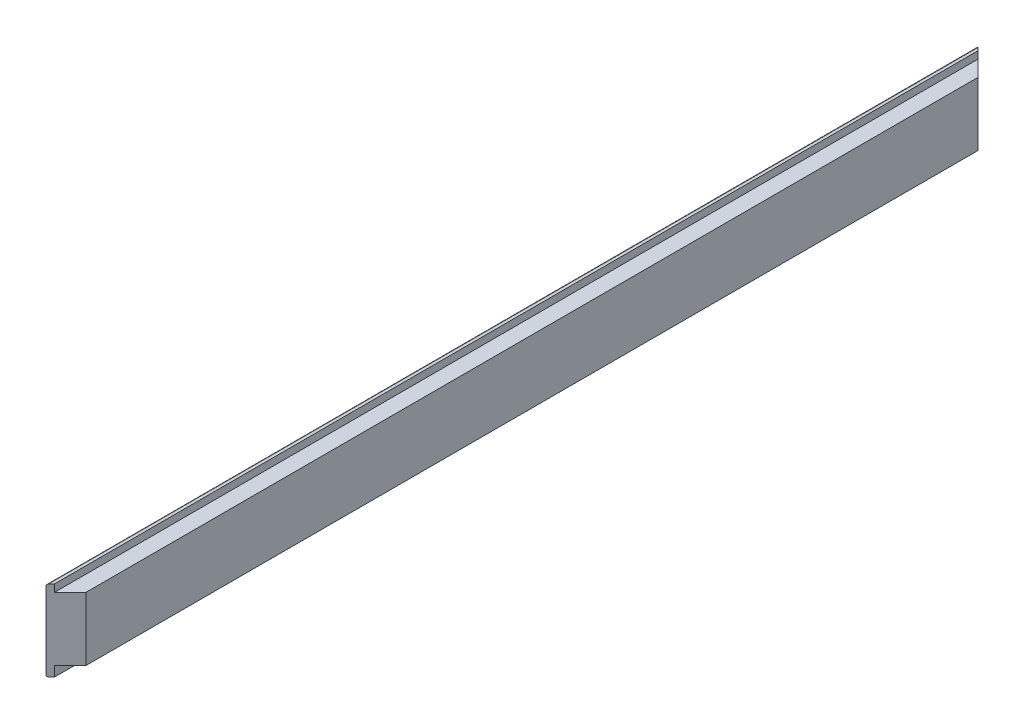
SolidWorks part; units mm, degrees
ref_plane "Front Plane" through (0, 0, 0) normal (0, 0, 1) x (1, 0, 0)
ref_plane "Top Plane" through (0, 0, 0) normal (0, 1, 0) x (1, 0, 0)
ref_plane "Right Plane" through (0, 0, 0) normal (1, 0, 0) x (0, 0, -1)
sketch "Sketch1" plane through (0, 0, 0) normal (0, 0, 1) x (1, 0, 0)
  line L1 (0, 0) -> (19.05, 0)
  line L2 (0, 0) -> (0, 77)
  line L3 (0, 77) -> (19.05, 77)
  line L4 (19.05, 0) -> (19.05, 77)
  line L5 (19.05, 77) -> (4.05, 77)
  line L6 (19.05, 77) -> (19.05, 70)
  line L7 (19.05, 70) -> (4.05, 70)
  line L8 (4.05, 77) -> (4.05, 70)
  line L9 (19.05, 0) -> (4.05, 0)
  line L10 (19.05, 0) -> (19.05, 9.525)
  line L11 (19.05, 9.525) -> (4.05, 9.525)
  line L12 (4.05, 0) -> (4.05, 9.525)
  dimension "D3" = 15
  dimension "D4" = 9.525
  dimension "D5" = 7
  dimension "D1" = 77
  dimension "D2" = 19.05
extrude "Boss-Extrude1" add sketch "Sketch1" along normal mid plane 889.1 contours L1 L12 L11 L4 L7 L8 L3 L2
fillet "Fillet1" radius 1.5875 2 edges at (0, 0, 0) (0, 77, 0)
sketch "Sketch2" plane through (0, 77, 0) normal (0, 1, 0) x (1, 0, 0)
  line L0 (0, -444.55) -> (19.05, -425.5)
  line L1 (19.05, -444.55) -> (19.05, 444.55) construction
  line L2 (19.05, -425.5) -> (19.05, -444.55)
  line L3 (19.05, -444.55) -> (0, -444.55)
  line L4 (0, 444.55) -> (19.05, 425.5)
  line L5 (19.05, 425.5) -> (19.05, 444.55)
  line L6 (19.05, 444.55) -> (0, 444.55)
extrude "Cut-Extrude1" cut sketch "Sketch2" against normal through all both and the other way through all
sketch "Sketch3" plane through (0, 9.525, 0) normal (0, -1, 0) x (1, 0, 0)
  line L0 (11.55, -425.5) -> (11.55, -410.5) construction
  line L1 (19.05, -425.5) -> (4.05, -425.5) construction
  line L3 (10.4775, 0) -> (-10.4775, 0) construction
  line L4 (4.05, 440.5) -> (4.05, -440.5) construction
  point P0 (11.55, -410.5)
  point P13 (11.55, 410.5)
  point P16 (11.55, 0)
  dimension "D1" = 15
hole_wizard "Ø7.9 (7.9) Diameter Hole1" positions "Sketch4" profile "Sketch5" hole size "Ø7.9" standard "ISO"
sketch "Sketch4" plane through (0, 9.525, 0) normal (0, -1, 0) x (-1, 0, 0)
  point P0 (-11.55, -410.5)
  point P3 (-11.55, 410.5)
  point P7 (-11.55, 0)
sketch "Sketch5" plane through (11.55, 9.525, 410.5) normal (1, 0, 0) x (0, 0, -1)
  line L0 (0, 0) -> (0, 17.3734)
  line L1 (0, 17.3734) -> (3.95, 15)
  line L2 (3.95, 15) -> (3.95, 0)
  line L5 (3.95, 0) -> (0, 0)
  line L10 (0, 17.3734) -> (-3.95, 15) construction
  line L11 (0, -6.35) -> (0, 107.95) construction
  dimension "Hole Dia." = 7.9
  dimension "Hole Depth" = 15
  dimension "Drill Angle" = 118
sketch "Sketch6" plane through (0, 0, 0) normal (-1, 0, 0) x (0, 0, 1)
  line L0 (378.1123, 33.9817) -> (356.26, 33.9817) construction
  line L1 (334.55, 50) -> (394.55, 50)
  line L2 (334.55, 50) -> (334.55, 20)
  line L3 (334.55, 20) -> (394.55, 20)
  line L4 (394.55, 50) -> (394.55, 20)
  line L5 (338.2336, 41.8089) -> (346.0737, 41.8089) construction
  line L6 (338.2336, 41.8089) -> (338.2336, 26.1544) construction
  line L7 (338.2336, 26.1544) -> (346.0737, 26.1544) construction
  line L8 (346.0737, 41.8089) -> (346.0737, 26.1544) construction
  line L9 (348.4199, 41.8089) -> (356.26, 41.8089) construction
  line L10 (348.4199, 41.8089) -> (348.4199, 26.1544) construction
  line L11 (348.4199, 26.1544) -> (356.26, 26.1544) construction
  line L12 (356.26, 41.8089) -> (356.26, 26.1544) construction
  line L13 (444.55, 1.5875) -> (444.55, 75.4125) construction
  line L15 (10.4775, 0) -> (-10.4775, 0) construction
  circle A6 centre (378.1123, 33.9817) radius 8.6938 construction
  dimension "D1" = 50
  dimension "D2" = 20
  dimension "D3" = 30
  dimension "D4" = 60
extrude "Cut-Extrude2" [suppressed] cut sketch "Sketch6" against normal through all both and the other way through all
equation "\"SquareSize\" = 5cm"
equation "\"TileCountX\"=12"
equation "\"TileCountY\"= 8"
equation "\"BottomBoardXSize\" = 880mm"
equation "\"BottomBoardYSize\" = 580mm"
equation "\"TopBoardXSize\" = 881mm"
equation "\"TopBoardYSize\"= 581mm"
equation "\"GantryHeight\"= 64mm"
equation "\"EncWallThickness\"= 5mm"
equation "\"EncLip\"= 15mm"
equation "\"TopBoardThickness\"= 3mm"
equation "\"BottomBoardThickness\"= .375in"
equation "\"D3@Sketch1\"=\"EncLip\""
equation "\"D4@Sketch1\"=\"BottomBoardThickness\""
equation "\"D5@Sketch1\"=7mm"
equation "\"D1@Boss-Extrude1\"=881+2*4.05000000"
equation "\"D1@Sketch1\"=\"GantryHeight\"+\"TopBoardThickness\"+10mm"
